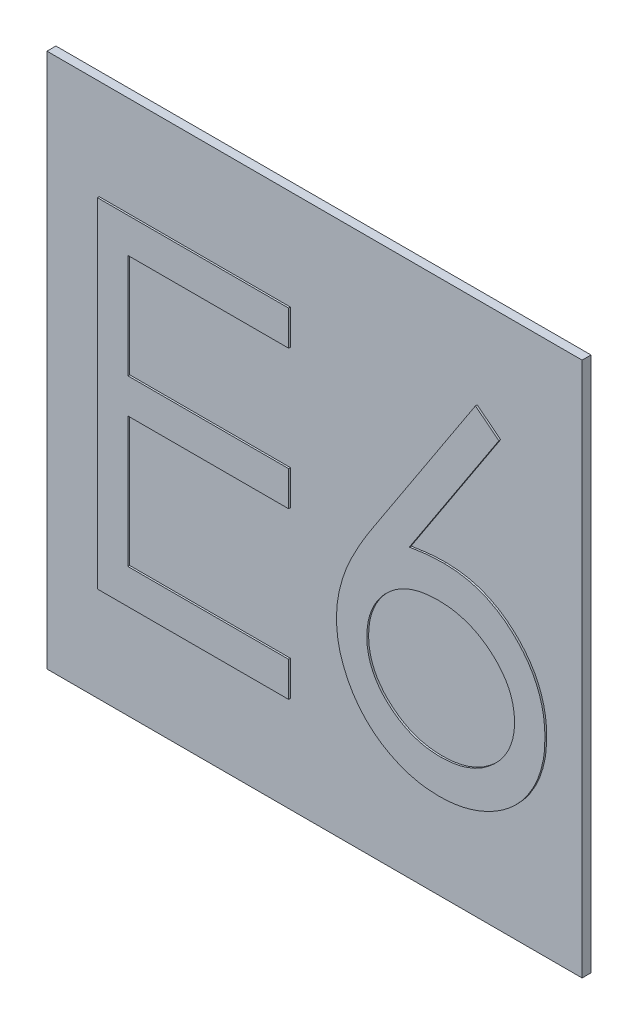
SolidWorks part; units mm, degrees
material "Custom Plastic"
ref_plane "Front Plane" through (0, 0, 0) normal (0, 0, 1) x (1, 0, 0)
ref_plane "Top Plane" through (0, 0, 0) normal (0, 1, 0) x (1, 0, 0)
ref_plane "Right Plane" through (0, 0, 0) normal (1, 0, 0) x (0, 0, -1)
sketch "Sketch1" plane through (0, 0, 0) normal (0, 0, 1) x (1, 0, 0)
  line L1 (0, 0) -> (76.2, 0)
  line L2 (0, 0) -> (0, 76.2)
  line L3 (0, 76.2) -> (76.2, 76.2)
  line L4 (76.2, 0) -> (76.2, 76.2)
  dimension "D1" = 76.2
  dimension "D2" = 76.2
extrude "Boss-Extrude1" add sketch "Sketch1" along normal blind 1.27
sketch "Sketch2" plane through (0, 0, 1.27) normal (0, 0, 1) x (1, 0, 0)
  text T0 "E6" font "Century Gothic" height 48.26
extrude "Boss-Extrude2" add sketch "Sketch2" along normal blind 0.254
